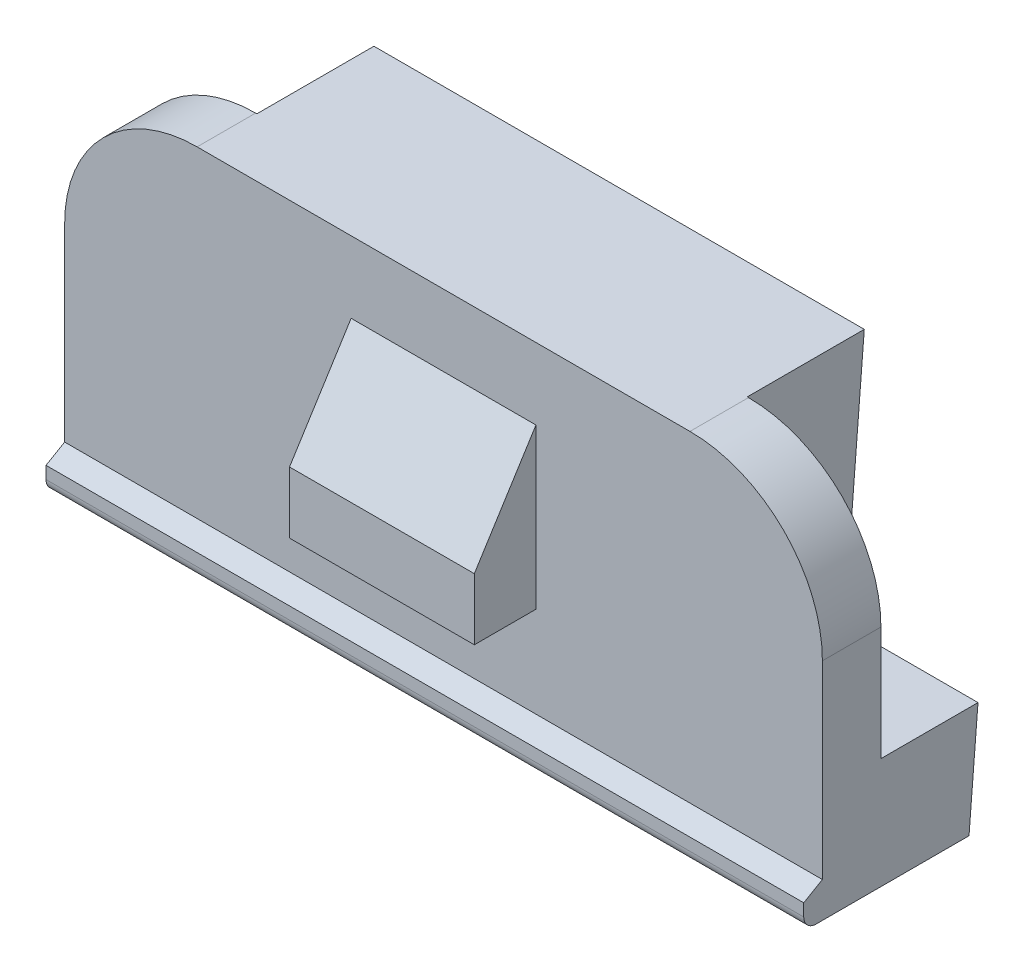
SolidWorks part; units mm, degrees
ref_plane "Front Plane" through (0, 0, 0) normal (0, 0, 1) x (1, 0, 0)
ref_plane "Top Plane" through (0, 0, 0) normal (0, 1, 0) x (1, 0, 0)
ref_plane "Right Plane" through (0, 0, 0) normal (1, 0, 0) x (0, 0, -1)
sketch "Sketch1" plane through (0, 0, 0) normal (1, 0, 0) x (0, 0, -1)
  line L0 (0, 0.2) -> (0, 0.4)
  line L1 (0, 0.4) -> (0.3031, 0.575)
  line L2 (0.3031, 0.575) -> (0.3031, 5.8)
  line L3 (0.3031, 5.8) -> (3.3031, 5.8)
  line L4 (3.3031, 5.8) -> (3.3031, 0)
  line L5 (3.3031, 0) -> (0.2, 0)
  arc A0 (0, 0.2) -> (0.2, 0) centre (0.2, 0.2) ccw
  point P9 (0, 0)
  dimension "D5" = 0.2
  dimension "D1" = 3
  dimension "D2" = 0.35
  dimension "D3" = 0.4
  dimension "D4" = 5.8
  dimension "D6" = 120
extrude "Boss-Extrude1" add sketch "Sketch1" along normal blind 12.3
sketch "Sketch2" plane through (0, 5.8, 0) normal (0, 1, 0) x (1, 0, 0)
  line L0 (6.15, 3.3031) -> (6.15, 0.3031) construction
  line L1 (0, 3.3031) -> (2.17, 3.3031)
  line L2 (0, 3.3031) -> (0, 1.2531)
  line L3 (0, 1.2531) -> (2.17, 1.2531)
  line L4 (2.17, 3.3031) -> (2.17, 1.2531)
  line L5 (12.3, 3.3031) -> (0, 3.3031) construction
  line L6 (12.3, 0.3031) -> (0, 0.3031) construction
  line L7 (12.3, 0.3031) -> (0, 0.3031) construction
  line L8 (12.3, 3.3031) -> (10.13, 3.3031)
  line L9 (12.3, 3.3031) -> (12.3, 1.2531)
  line L10 (12.3, 1.2531) -> (10.13, 1.2531)
  line L11 (10.13, 3.3031) -> (10.13, 1.2531)
  dimension "D1" = 0.95
  dimension "D2" = 7.96
extrude "Cut-Extrude1" cut sketch "Sketch2" against normal blind 4
fillet "Fillet1" radius 2.15 2 edges at (12.3, 5.8, -0.7781) (0, 5.8, -0.7781)
sketch "Sketch4" plane through (0, 0, -0.3031) normal (0, 0, 1) x (1, 0, 0)
  line L0 (6.15, 5.8) -> (6.15, 0.575) construction
  line L1 (10.15, 5.8) -> (2.15, 5.8) construction
  line L2 (12.3, 0.575) -> (0, 0.575) construction
  line L4 (4.65, 3.05) -> (7.65, 3.05)
  line L5 (4.65, 3.05) -> (4.65, 2.05)
  line L6 (4.65, 2.05) -> (7.65, 2.05)
  line L7 (7.65, 3.05) -> (7.65, 2.05)
  line L8 (4.65, 3.05) -> (7.65, 2.05) construction
  line L9 (4.65, 2.05) -> (7.65, 3.05) construction
  point P6 (6.15, 2.55)
  dimension "D1" = 3
  dimension "D2" = 1
  dimension "D3" = 3.75
extrude "Boss-Extrude2" add sketch "Sketch4" along normal blind 1
sketch "Sketch5" plane through (7.65, 0, 0) normal (1, 0, 0) x (0, 0, -1)
  line L0 (-0.6969, 3.05) -> (0.3031, 3.05)
  line L1 (0.3031, 3.05) -> (0.3031, 4.64)
  line L3 (0.3031, 5.8) -> (0.3031, 3.65) construction
  line L4 (0.3031, 4.64) -> (-0.6969, 3.05)
  dimension "D1" = 1.59
extrude "Boss-Extrude3" add sketch "Sketch5" against normal up to surface (3 mm away) up to face at (4.65, 2.55, 0.1969)
sketch "Sketch7" plane through (12.3, 0, 0) normal (1, 0, 0) x (0, 0, -1)
  line L0 (3.3031, 5.8) -> (3.3031, 0)
  line L1 (3.3031, 0) -> (2.6831, 0)
  line L2 (0.2, 0) -> (3.3031, 0) construction
  line L3 (2.6831, 0) -> (3.1531, 5.8)
  line L4 (3.3031, 5.8) -> (1.2531, 5.8) construction
  line L5 (3.1531, 5.8) -> (3.3031, 5.8)
  line L6 (0.3031, 5.8) -> (0.3031, 3.65) construction
  line L7 (0.3031, 3.65) -> (0.3031, 0.575) construction
  dimension "D1" = 2.85
  dimension "D2" = 2.38
extrude "Cut-Extrude2" cut sketch "Sketch7" against normal through all
